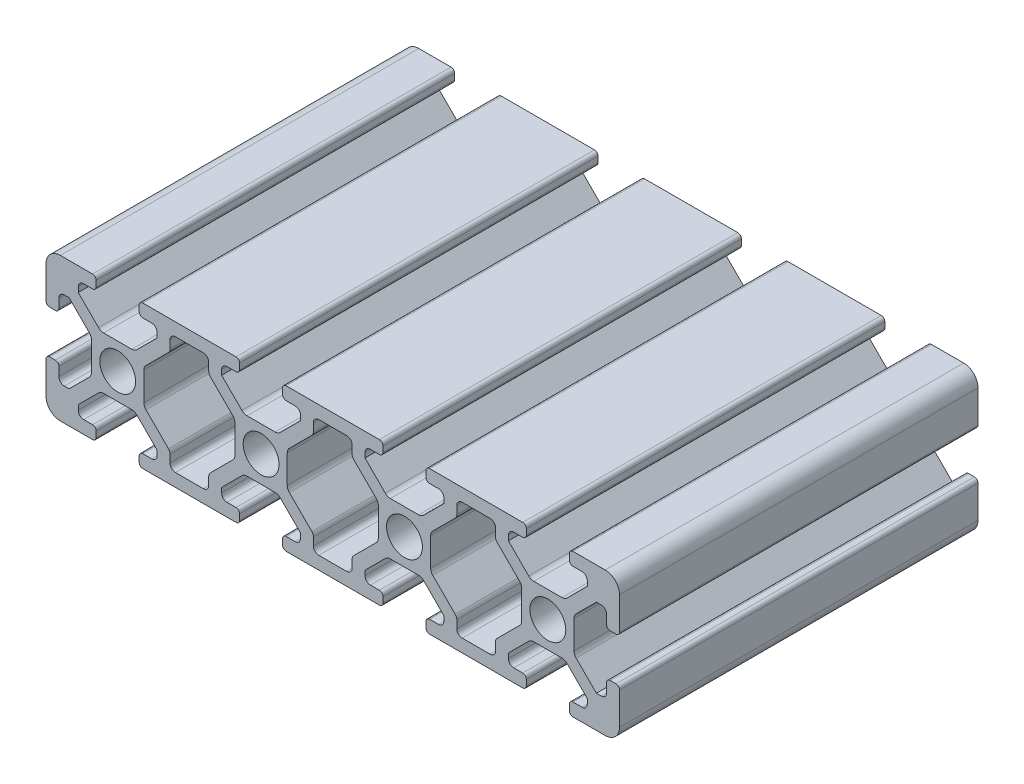
SolidWorks part; units mm, degrees
material "6063-T5"
ref_plane "Front Plane" through (0, 0, 0) normal (0, 0, 1) x (1, 0, 0)
ref_plane "Top Plane" through (0, 0, 0) normal (0, 1, 0) x (1, 0, 0)
ref_plane "Right Plane" through (0, 0, 0) normal (1, 0, 0) x (0, 0, -1)
sketch "Sketch1" plane through (0, 0, 0) normal (0, 0, 1) x (1, 0, 0)
  line L0 (2, 0) -> (6.5, 0)
  line L1 (80, 2) -> (80, 6.5)
  line L2 (78, 20) -> (73.5, 20)
  line L3 (0, 18) -> (0, 13.5)
  line L4 (33, 19.5) -> (33, 18.7)
  line L5 (27, 19.5) -> (27, 18.7)
  line L6 (7, 19.5) -> (7, 18.7)
  line L7 (13, 19.5) -> (13, 18.7)
  line L8 (6.5, 20) -> (2, 20)
  line L9 (53, 19.5) -> (53, 18.7)
  line L10 (47, 19.5) -> (47, 18.7)
  line L11 (73, 19.5) -> (73, 18.7)
  line L12 (67, 19.5) -> (67, 18.7)
  line L13 (33, 1.3) -> (33, 0.5)
  line L14 (27, 1.3) -> (27, 0.5)
  line L15 (53, 1.3) -> (53, 0.5)
  line L16 (47, 1.3) -> (47, 0.5)
  line L17 (73, 1.3) -> (73, 0.5)
  line L18 (67, 1.3) -> (67, 0.5)
  line L19 (13, 1.3) -> (13, 0.5)
  line L20 (7, 1.3) -> (7, 0.5)
  line L21 (13.5, 20) -> (26.5, 20) construction
  line L22 (26.5, 20) -> (13.5, 20)
  line L23 (46.5, 20) -> (33.5, 20)
  line L24 (66.5, 20) -> (53.5, 20)
  line L25 (73.5, 0) -> (78, 0)
  line L26 (53.5, 0) -> (66.5, 0)
  line L27 (33.5, 0) -> (46.5, 0)
  line L28 (13.5, 0) -> (26.5, 0)
  line L29 (79.5, 13) -> (78.7, 13)
  line L30 (79.5, 7) -> (78.7, 7)
  line L31 (0.5, 13) -> (1.3, 13)
  line L32 (0.5, 7) -> (1.3, 7)
  line L33 (0, 6.5) -> (0, 2)
  line L34 (80, 13.5) -> (80, 18)
  line L35 (1.8, 13.5) -> (1.8, 14.75)
  line L36 (5.25, 18.2) -> (6.5, 18.2)
  line L37 (78.2, 14.75) -> (78.2, 13.5)
  line L38 (74.75, 1.8) -> (73.5, 1.8)
  line L39 (1.8, 5.25) -> (1.8, 6.5)
  line L40 (13.5, 18.2) -> (14.75, 18.2)
  line L41 (6.5, 1.8) -> (5.25, 1.8)
  line L42 (33.5, 18.2) -> (34.75, 18.2)
  line L43 (26.5, 1.8) -> (25.25, 1.8)
  line L44 (53.5, 18.2) -> (54.75, 18.2)
  line L45 (46.5, 1.8) -> (45.25, 1.8)
  line L46 (73.5, 18.2) -> (74.75, 18.2)
  line L47 (66.5, 1.8) -> (65.25, 1.8)
  line L48 (78.2, 6.5) -> (78.2, 5.25)
  line L49 (12.6701, 13.9429) -> (15.5, 16.7728)
  line L50 (12.6701, 6.0571) -> (15.5, 3.2272)
  line L51 (32.6701, 13.9429) -> (35.5, 16.7728)
  line L52 (33.9429, 12.6701) -> (37.0803, 15.8075)
  line L53 (27.3299, 13.9429) -> (24.5, 16.7728)
  line L54 (22.9197, 15.8075) -> (26.0571, 12.6701)
  line L55 (27.3299, 6.0571) -> (24.5, 3.2272)
  line L56 (22.9197, 4.1925) -> (26.0571, 7.3299)
  line L57 (47.3299, 13.9429) -> (44.5, 16.7728)
  line L58 (42.9197, 15.8075) -> (46.0571, 12.6701)
  line L59 (47.3299, 6.0571) -> (44.5, 3.2272)
  line L60 (42.9197, 4.1925) -> (46.0571, 7.3299)
  line L61 (67.3299, 13.9429) -> (64.5, 16.7728)
  line L62 (62.9197, 15.8075) -> (66.0571, 12.6701)
  line L63 (67.3299, 6.0571) -> (64.5, 3.2272)
  line L64 (62.9197, 4.1925) -> (66.0571, 7.3299)
  line L65 (33.9429, 7.3299) -> (37.0803, 4.1925)
  line L66 (13.9429, 12.6701) -> (17.0803, 15.8075)
  line L67 (6.0571, 7.3299) -> (3.2272, 4.5)
  line L68 (7.3299, 6.0571) -> (4.5, 3.2272)
  line L69 (7.3299, 13.9429) -> (4.5, 16.7728)
  line L70 (32.6701, 6.0571) -> (35.5, 3.2272)
  line L71 (13.9429, 7.3299) -> (17.0803, 4.1925)
  line L72 (52.6701, 13.9429) -> (55.5, 16.7728)
  line L73 (6.0571, 12.6701) -> (3.2272, 15.5)
  line L74 (53.9429, 12.6701) -> (57.0803, 15.8075)
  line L75 (53.9429, 7.3299) -> (57.0803, 4.1925)
  line L76 (52.6701, 6.0571) -> (55.5, 3.2272)
  line L77 (72.6701, 13.9429) -> (75.5, 16.7728)
  line L78 (73.9429, 12.6701) -> (76.7728, 15.5)
  line L79 (73.9429, 7.3299) -> (76.7728, 4.5)
  line L80 (72.6701, 6.0571) -> (75.5, 3.2272)
  line L81 (28.037, 13.65) -> (31.963, 13.65)
  line L82 (18.05, 18.2) -> (21.95, 18.2)
  line L83 (14.75, 1.8) -> (13.5, 1.8)
  line L84 (15.5, 17.45) -> (15.5, 16.7728)
  line L85 (34.75, 1.8) -> (33.5, 1.8)
  line L86 (4.5, 17.45) -> (4.5, 16.7728)
  line L87 (54.75, 1.8) -> (53.5, 1.8)
  line L88 (24.5, 17.45) -> (24.5, 16.7728)
  line L89 (27.7144, 8.9872) -> (21.8, 3.0728) [skipped]
  line L90 (25.25, 18.2) -> (26.5, 18.2)
  line L91 (27.7144, 11.0128) -> (21.8, 16.9272) [skipped]
  line L92 (45.25, 18.2) -> (46.5, 18.2)
  line L93 (33.65, 11.963) -> (33.65, 8.037)
  line L94 (31.963, 6.35) -> (28.037, 6.35)
  line L95 (26.35, 8.037) -> (26.35, 11.963)
  line L96 (65.25, 18.2) -> (66.5, 18.2)
  line L97 (44.5, 17.45) -> (44.5, 16.7728)
  line L98 (35.5, 17.45) -> (35.5, 16.7728)
  line L99 (47.7144, 8.9872) -> (41.8, 3.0728) [skipped]
  line L100 (47.7144, 11.0128) -> (41.8, 16.9272) [skipped]
  line L101 (67.7144, 11.0128) -> (61.8, 16.9272) [skipped]
  line L102 (67.7144, 8.9872) -> (61.8, 3.0728) [skipped]
  line L103 (13.65, 11.963) -> (13.65, 8.037)
  line L104 (11.963, 6.35) -> (8.037, 6.35)
  line L105 (6.35, 8.037) -> (6.35, 11.963)
  line L106 (8.037, 13.65) -> (11.963, 13.65)
  line L107 (48.037, 13.65) -> (51.963, 13.65)
  line L108 (53.65, 11.963) -> (53.65, 8.037)
  line L109 (51.963, 6.35) -> (48.037, 6.35)
  line L110 (46.35, 8.037) -> (46.35, 11.963)
  line L111 (68.037, 13.65) -> (71.963, 13.65)
  line L112 (73.65, 11.963) -> (73.65, 8.037)
  line L113 (71.963, 6.35) -> (68.037, 6.35)
  line L114 (66.35, 8.037) -> (66.35, 11.963)
  line L115 (64.5, 17.45) -> (64.5, 16.7728)
  line L116 (55.5, 17.45) -> (55.5, 16.7728)
  line L117 (4.5, 2.55) -> (4.5, 3.2272)
  line L118 (75.5, 17.45) -> (75.5, 16.7728)
  line L119 (24.5, 2.55) -> (24.5, 3.2272)
  line L120 (15.5, 2.55) -> (15.5, 3.2272)
  line L121 (44.5, 2.55) -> (44.5, 3.2272)
  line L122 (35.5, 2.55) -> (35.5, 3.2272)
  line L123 (64.5, 2.55) -> (64.5, 3.2272)
  line L124 (55.5, 2.55) -> (55.5, 3.2272)
  line L125 (2.55, 15.5) -> (3.2272, 15.5)
  line L126 (75.5, 2.55) -> (75.5, 3.2272)
  line L127 (2.55, 4.5) -> (3.2272, 4.5)
  line L128 (77.45, 15.5) -> (76.7728, 15.5)
  line L129 (17.3, 17.45) -> (17.3, 16.3379)
  line L130 (77.45, 4.5) -> (76.7728, 4.5)
  line L131 (22.7, 17.45) -> (22.7, 16.3379)
  line L132 (38.05, 18.2) -> (41.95, 18.2)
  line L133 (37.3, 17.45) -> (37.3, 16.3379)
  line L134 (42.7, 17.45) -> (42.7, 16.3379)
  line L135 (58.05, 18.2) -> (61.95, 18.2)
  line L136 (57.3, 17.45) -> (57.3, 16.3379)
  line L137 (62.7, 17.45) -> (62.7, 16.3379)
  line L138 (17.3, 3.6621) -> (17.3, 2.55)
  line L139 (18.05, 1.8) -> (21.95, 1.8)
  line L140 (22.7, 2.55) -> (22.7, 3.6621)
  line L141 (37.3, 3.6621) -> (37.3, 2.55)
  line L142 (38.05, 1.8) -> (41.95, 1.8)
  line L143 (42.7, 2.55) -> (42.7, 3.6621)
  line L144 (57.3, 3.6621) -> (57.3, 2.55)
  line L145 (58.05, 1.8) -> (61.95, 1.8)
  line L146 (62.7, 2.55) -> (62.7, 3.6621)
  circle A0 centre (10, 10) radius 2.5
  circle A1 centre (30, 10) radius 2.5
  circle A2 centre (50, 10) radius 2.5
  circle A3 centre (70, 10) radius 2.5
  arc A4 (78, 0) -> (80, 2) centre (78, 2) ccw
  arc A5 (80, 18) -> (78, 20) centre (78, 18) ccw
  arc A6 (2, 0) -> (0, 2) centre (2, 2) cw
  arc A7 (2, 20) -> (0, 18) centre (2, 18) ccw
  arc A8 (12.6701, 13.9429) -> (11.963, 13.65) centre (11.963, 14.65) cw
  arc A9 (7.3299, 13.9429) -> (8.037, 13.65) centre (8.037, 14.65) ccw
  arc A10 (6.0571, 12.6701) -> (6.35, 11.963) centre (5.35, 11.963) cw
  arc A11 (6.0571, 7.3299) -> (6.35, 8.037) centre (5.35, 8.037) ccw
  arc A12 (7.3299, 6.0571) -> (8.037, 6.35) centre (8.037, 5.35) cw
  arc A13 (12.6701, 6.0571) -> (11.963, 6.35) centre (11.963, 5.35) ccw
  arc A14 (32.6701, 6.0571) -> (31.963, 6.35) centre (31.963, 5.35) ccw
  arc A15 (27.3299, 6.0571) -> (28.037, 6.35) centre (28.037, 5.35) cw
  arc A16 (27.3299, 13.9429) -> (28.037, 13.65) centre (28.037, 14.65) ccw
  arc A17 (32.6701, 13.9429) -> (31.963, 13.65) centre (31.963, 14.65) cw
  arc A18 (47.3299, 6.0571) -> (48.037, 6.35) centre (48.037, 5.35) cw
  arc A19 (52.6701, 6.0571) -> (51.963, 6.35) centre (51.963, 5.35) ccw
  arc A20 (52.6701, 13.9429) -> (51.963, 13.65) centre (51.963, 14.65) cw
  arc A21 (47.3299, 13.9429) -> (48.037, 13.65) centre (48.037, 14.65) ccw
  arc A22 (72.6701, 13.9429) -> (71.963, 13.65) centre (71.963, 14.65) cw
  arc A23 (67.3299, 13.9429) -> (68.037, 13.65) centre (68.037, 14.65) ccw
  arc A24 (67.3299, 6.0571) -> (68.037, 6.35) centre (68.037, 5.35) cw
  arc A25 (72.6701, 6.0571) -> (71.963, 6.35) centre (71.963, 5.35) ccw
  arc A26 (73.9429, 7.3299) -> (73.65, 8.037) centre (74.65, 8.037) cw
  arc A27 (73.9429, 12.6701) -> (73.65, 11.963) centre (74.65, 11.963) ccw
  arc A28 (66.0571, 7.3299) -> (66.35, 8.037) centre (65.35, 8.037) ccw
  arc A29 (66.0571, 12.6701) -> (66.35, 11.963) centre (65.35, 11.963) cw
  arc A30 (53.9429, 7.3299) -> (53.65, 8.037) centre (54.65, 8.037) cw
  arc A31 (53.9429, 12.6701) -> (53.65, 11.963) centre (54.65, 11.963) ccw
  arc A32 (78.2, 14.75) -> (77.45, 15.5) centre (77.45, 14.75) ccw
  arc A33 (75.5, 17.45) -> (74.75, 18.2) centre (74.75, 17.45) ccw
  arc A34 (78.2, 5.25) -> (77.45, 4.5) centre (77.45, 5.25) cw
  arc A35 (75.5, 2.55) -> (74.75, 1.8) centre (74.75, 2.55) cw
  arc A36 (46.0571, 7.3299) -> (46.35, 8.037) centre (45.35, 8.037) ccw
  arc A37 (46.0571, 12.6701) -> (46.35, 11.963) centre (45.35, 11.963) cw
  arc A38 (33.9429, 7.3299) -> (33.65, 8.037) centre (34.65, 8.037) cw
  arc A39 (33.9429, 12.6701) -> (33.65, 11.963) centre (34.65, 11.963) ccw
  arc A40 (13.9429, 12.6701) -> (13.65, 11.963) centre (14.65, 11.963) ccw
  arc A41 (13.9429, 7.3299) -> (13.65, 8.037) centre (14.65, 8.037) cw
  arc A42 (26.0571, 7.3299) -> (26.35, 8.037) centre (25.35, 8.037) ccw
  arc A43 (26.0571, 12.6701) -> (26.35, 11.963) centre (25.35, 11.963) cw
  arc A44 (65.25, 1.8) -> (64.5, 2.55) centre (65.25, 2.55) cw
  arc A45 (61.95, 1.8) -> (62.7, 2.55) centre (61.95, 2.55) ccw
  arc A46 (57.3, 2.55) -> (58.05, 1.8) centre (58.05, 2.55) ccw
  arc A47 (54.75, 1.8) -> (55.5, 2.55) centre (54.75, 2.55) ccw
  arc A48 (45.25, 1.8) -> (44.5, 2.55) centre (45.25, 2.55) cw
  arc A49 (64.5, 17.45) -> (65.25, 18.2) centre (65.25, 17.45) cw
  arc A50 (61.95, 18.2) -> (62.7, 17.45) centre (61.95, 17.45) cw
  arc A51 (58.05, 18.2) -> (57.3, 17.45) centre (58.05, 17.45) ccw
  arc A52 (53, 18.7) -> (53.5, 18.2) centre (53.5, 18.7) ccw
  arc A53 (53, 19.5) -> (53.5, 20) centre (53.5, 19.5) cw
  arc A54 (67, 18.7) -> (66.5, 18.2) centre (66.5, 18.7) cw
  arc A55 (67, 19.5) -> (66.5, 20) centre (66.5, 19.5) ccw
  arc A56 (73, 18.7) -> (73.5, 18.2) centre (73.5, 18.7) ccw
  arc A57 (73, 19.5) -> (73.5, 20) centre (73.5, 19.5) cw
  arc A58 (78.7, 13) -> (78.2, 13.5) centre (78.7, 13.5) cw
  arc A59 (79.5, 13) -> (80, 13.5) centre (79.5, 13.5) ccw
  arc A60 (78.7, 7) -> (78.2, 6.5) centre (78.7, 6.5) ccw
  arc A61 (79.5, 7) -> (80, 6.5) centre (79.5, 6.5) cw
  arc A62 (73, 0.5) -> (73.5, 0) centre (73.5, 0.5) ccw
  arc A63 (73, 1.3) -> (73.5, 1.8) centre (73.5, 1.3) cw
  arc A64 (67, 0.5) -> (66.5, 0) centre (66.5, 0.5) cw
  arc A65 (67, 1.3) -> (66.5, 1.8) centre (66.5, 1.3) ccw
  arc A66 (53, 0.5) -> (53.5, 0) centre (53.5, 0.5) ccw
  arc A67 (53, 1.3) -> (53.5, 1.8) centre (53.5, 1.3) cw
  arc A68 (47, 0.5) -> (46.5, 0) centre (46.5, 0.5) cw
  arc A69 (47, 1.3) -> (46.5, 1.8) centre (46.5, 1.3) ccw
  arc A70 (33, 0.5) -> (33.5, 0) centre (33.5, 0.5) ccw
  arc A71 (33, 1.3) -> (33.5, 1.8) centre (33.5, 1.3) cw
  arc A72 (27, 0.5) -> (26.5, 0) centre (26.5, 0.5) cw
  arc A73 (27, 1.3) -> (26.5, 1.8) centre (26.5, 1.3) ccw
  arc A74 (47, 18.7) -> (46.5, 18.2) centre (46.5, 18.7) cw
  arc A75 (47, 19.5) -> (46.5, 20) centre (46.5, 19.5) ccw
  arc A76 (33, 18.7) -> (33.5, 18.2) centre (33.5, 18.7) ccw
  arc A77 (33, 19.5) -> (33.5, 20) centre (33.5, 19.5) cw
  arc A78 (27, 18.7) -> (26.5, 18.2) centre (26.5, 18.7) cw
  arc A79 (27, 19.5) -> (26.5, 20) centre (26.5, 19.5) ccw
  arc A80 (13, 18.7) -> (13.5, 18.2) centre (13.5, 18.7) ccw
  arc A81 (13.5, 20) -> (13, 19.5) centre (13.5, 19.5) ccw
  arc A82 (13, 0.5) -> (13.5, 0) centre (13.5, 0.5) ccw
  arc A83 (13, 1.3) -> (13.5, 1.8) centre (13.5, 1.3) cw
  arc A84 (7, 0.5) -> (6.5, 0) centre (6.5, 0.5) cw
  arc A85 (7, 1.3) -> (6.5, 1.8) centre (6.5, 1.3) ccw
  arc A86 (0, 6.5) -> (0.5, 7) centre (0.5, 6.5) cw
  arc A87 (1.3, 7) -> (1.8, 6.5) centre (1.3, 6.5) cw
  arc A88 (0, 13.5) -> (0.5, 13) centre (0.5, 13.5) ccw
  arc A89 (1.3, 13) -> (1.8, 13.5) centre (1.3, 13.5) ccw
  arc A90 (6.5, 20) -> (7, 19.5) centre (6.5, 19.5) cw
  arc A91 (7, 18.7) -> (6.5, 18.2) centre (6.5, 18.7) cw
  arc A92 (55.5, 17.45) -> (54.75, 18.2) centre (54.75, 17.45) ccw
  arc A93 (44.5, 17.45) -> (45.25, 18.2) centre (45.25, 17.45) cw
  arc A94 (37.3, 2.55) -> (38.05, 1.8) centre (38.05, 2.55) ccw
  arc A95 (38.05, 18.2) -> (37.3, 17.45) centre (38.05, 17.45) ccw
  arc A96 (41.95, 18.2) -> (42.7, 17.45) centre (41.95, 17.45) cw
  arc A97 (41.95, 1.8) -> (42.7, 2.55) centre (41.95, 2.55) ccw
  arc A98 (34.75, 1.8) -> (35.5, 2.55) centre (34.75, 2.55) ccw
  arc A99 (25.25, 1.8) -> (24.5, 2.55) centre (25.25, 2.55) cw
  arc A100 (14.75, 1.8) -> (15.5, 2.55) centre (14.75, 2.55) ccw
  arc A101 (5.25, 1.8) -> (4.5, 2.55) centre (5.25, 2.55) cw
  arc A102 (2.55, 4.5) -> (1.8, 5.25) centre (2.55, 5.25) cw
  arc A103 (1.8, 14.75) -> (2.55, 15.5) centre (2.55, 14.75) cw
  arc A104 (24.5, 17.45) -> (25.25, 18.2) centre (25.25, 17.45) cw
  arc A105 (34.75, 18.2) -> (35.5, 17.45) centre (34.75, 17.45) cw
  arc A106 (21.95, 18.2) -> (22.7, 17.45) centre (21.95, 17.45) cw
  arc A107 (18.05, 18.2) -> (17.3, 17.45) centre (18.05, 17.45) ccw
  arc A108 (15.5, 17.45) -> (14.75, 18.2) centre (14.75, 17.45) ccw
  arc A109 (5.25, 18.2) -> (4.5, 17.45) centre (5.25, 17.45) ccw
  arc A110 (62.7, 3.6621) -> (62.9197, 4.1925) centre (63.45, 3.6621) cw
  arc A111 (57.3, 3.6621) -> (57.0803, 4.1925) centre (56.55, 3.6621) ccw
  arc A112 (62.7, 16.3379) -> (62.9197, 15.8075) centre (63.45, 16.3379) ccw
  arc A113 (57.3, 16.3379) -> (57.0803, 15.8075) centre (56.55, 16.3379) cw
  arc A114 (42.7, 3.6621) -> (42.9197, 4.1925) centre (43.45, 3.6621) cw
  arc A115 (37.3, 3.6621) -> (37.0803, 4.1925) centre (36.55, 3.6621) ccw
  arc A116 (42.7, 16.3379) -> (42.9197, 15.8075) centre (43.45, 16.3379) ccw
  arc A117 (37.3, 16.3379) -> (37.0803, 15.8075) centre (36.55, 16.3379) cw
  arc A118 (22.7, 16.3379) -> (22.9197, 15.8075) centre (23.45, 16.3379) ccw
  arc A119 (17.3, 16.3379) -> (17.0803, 15.8075) centre (16.55, 16.3379) cw
  arc A120 (17.3, 3.6621) -> (17.0803, 4.1925) centre (16.55, 3.6621) ccw
  arc A121 (22.7, 3.6621) -> (22.9197, 4.1925) centre (23.45, 3.6621) cw
  arc A122 (21.95, 1.8) -> (22.7, 2.55) centre (21.95, 2.55) ccw
  arc A123 (17.3, 2.55) -> (18.05, 1.8) centre (18.05, 2.55) ccw
  point P124 (0, 0)
  point P394 (17.3, 16.0272)
  dimension "D1" = 4
  dimension "D3" = 4
  dimension "D2" = 2
  dimension "D4" = 3
extrude "Boss-Extrude1" add sketch "Sketch1" along normal blind 50
